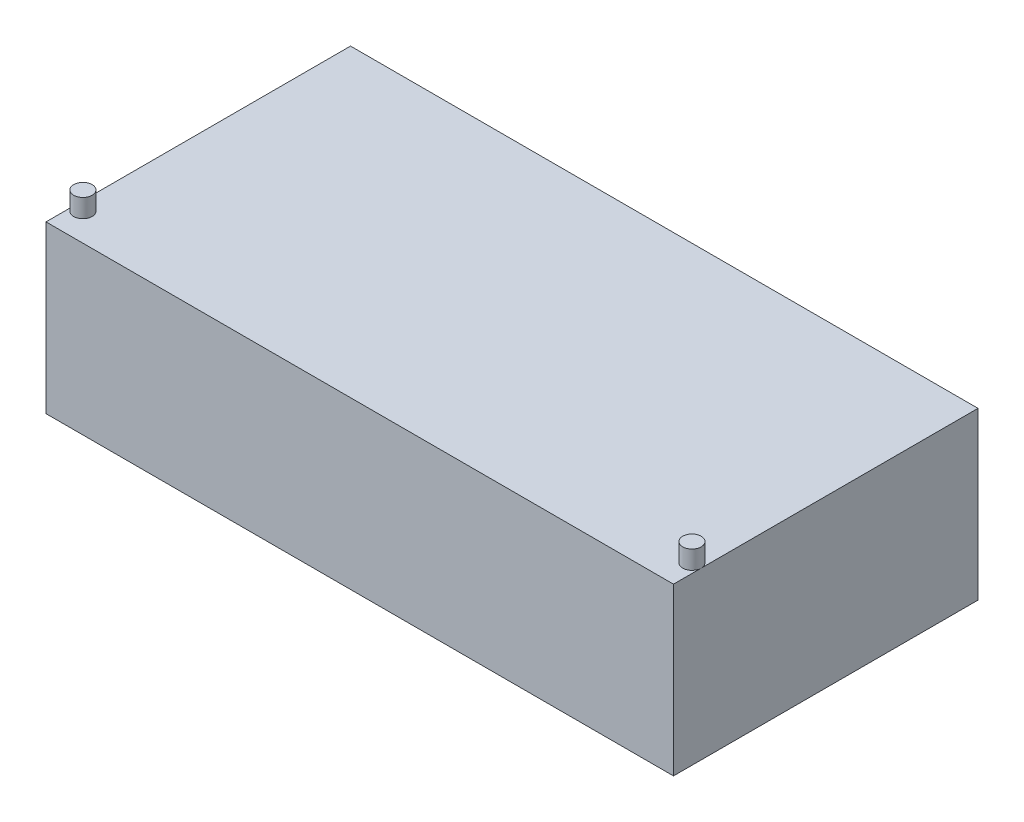
SolidWorks part; units mm, degrees
material "Custom Plastic"
ref_plane "Front Plane" through (0, 0, 0) normal (0, 0, 1) x (1, 0, 0)
ref_plane "Top Plane" through (0, 0, 0) normal (0, 1, 0) x (1, 0, 0)
ref_plane "Right Plane" through (0, 0, 0) normal (1, 0, 0) x (0, 0, -1)
sketch "Sketch1" plane through (0, 0, 0) normal (0, 1, 0) x (1, 0, 0)
  line L1 (-170, 82.5) -> (170, 82.5)
  line L2 (-170, 82.5) -> (-170, -82.5)
  line L3 (-170, -82.5) -> (170, -82.5)
  line L4 (170, 82.5) -> (170, -82.5)
  line L5 (-170, 82.5) -> (170, -82.5) construction
  line L6 (-170, -82.5) -> (170, 82.5) construction
  point P0 (0, 0)
  dimension "D1" = 165
  dimension "D2" = 340
extrude "Boss-Extrude1" add sketch "Sketch1" along normal blind 90
sketch "Sketch2" plane through (0, 90, 0) normal (0, 1, 0) x (1, 0, 0)
  circle A0 centre (-165, -67.5) radius 5
  circle A1 centre (165, -67.5) radius 5
extrude "Boss-Extrude2" add sketch "Sketch2" along normal blind 10
